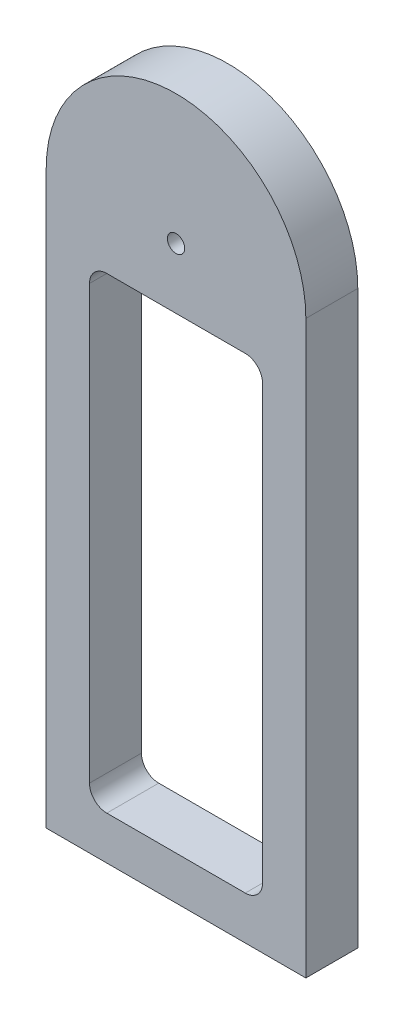
SolidWorks part; units mm, degrees
material "Gray Cast Iron"
ref_plane "Front Plane" through (0, 0, 0) normal (0, 0, 1) x (1, 0, 0)
ref_plane "Top Plane" through (0, 0, 0) normal (0, 1, 0) x (1, 0, 0)
ref_plane "Right Plane" through (0, 0, 0) normal (1, 0, 0) x (0, 0, -1)
sketch "Sketch1" plane through (0, 0, 0) normal (0, 0, 1) x (1, 0, 0)
  line L0 (0, 0) -> (150, 0)
  line L1 (150, 0) -> (150, 330)
  line L3 (0, 330) -> (0, 0)
  line L4 (75, 0) -> (75, 25)
  line L5 (25, 25) -> (125, 25)
  line L6 (125, 25) -> (125, 295)
  line L7 (125, 295) -> (25, 295)
  line L8 (25, 295) -> (25, 25)
  arc A0 (0, 330) -> (150, 330) centre (75, 330) cw
  circle A1 centre (75, 330) radius 5
  point P12 (75, 25)
  dimension "D3" = 10
  dimension "D1" = 150
  dimension "D2" = 330
  dimension "D4" = 25
  dimension "D5" = 100
  dimension "D6" = 270
extrude "Boss-Extrude1" add sketch "Sketch1" along normal blind 30
fillet "Fillet1" radius 10 4 edges at (125, 25, 15) (125, 295, 15) (25, 295, 15) (25, 25, 15)
